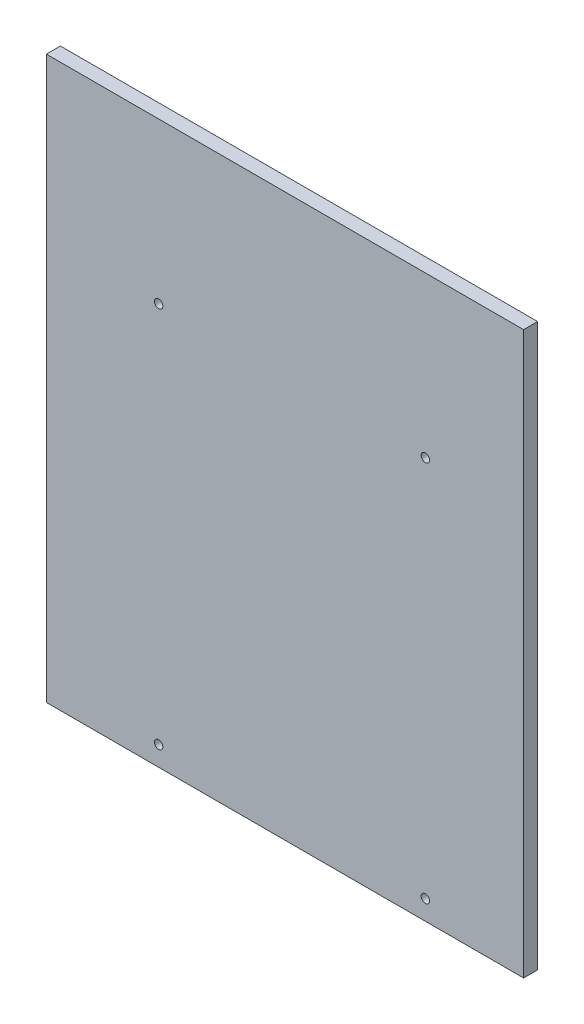
SolidWorks part; units mm, degrees
ref_plane "Front Plane" through (0, 0, 0) normal (0, 0, 1) x (1, 0, 0)
ref_plane "Top Plane" through (0, 0, 0) normal (0, 1, 0) x (1, 0, 0)
ref_plane "Right Plane" through (0, 0, 0) normal (1, 0, 0) x (0, 0, -1)
sketch "Sketch1" plane through (0, 0, 0) normal (0, 0, 1) x (1, 0, 0)
  line L0 (50, -100) -> (50, 100) construction
  line L1 (-85, -100) -> (85, -100)
  line L2 (-85, -100) -> (-85, 100)
  line L3 (-85, 100) -> (85, 100)
  line L4 (85, -100) -> (85, 100)
  line L5 (-85, -100) -> (85, 100) construction
  line L6 (-85, 100) -> (85, -100) construction
  line L7 (-45, -100) -> (-45, 100) construction
  line L8 (85, -93) -> (-56.4117, -93) construction
  line L9 (85, 43) -> (-56.4117, 43) construction
  circle A0 centre (-45, 43) radius 1.5
  circle A1 centre (50, 43) radius 1.5
  circle A2 centre (50, -93) radius 1.5
  circle A3 centre (-45, -93) radius 1.5
  point P0 (0, 0)
  point P22 (0, 0)
  point P24 (0, 0)
  point P25 (0, 0)
  dimension "D7" = 3
  dimension "D1" = 170
  dimension "D2" = 200
  dimension "D3" = 7
  dimension "D4" = 35
  dimension "D5" = 95
  dimension "D6" = 136
extrude "Boss-Extrude1" add sketch "Sketch1" along normal blind 5
